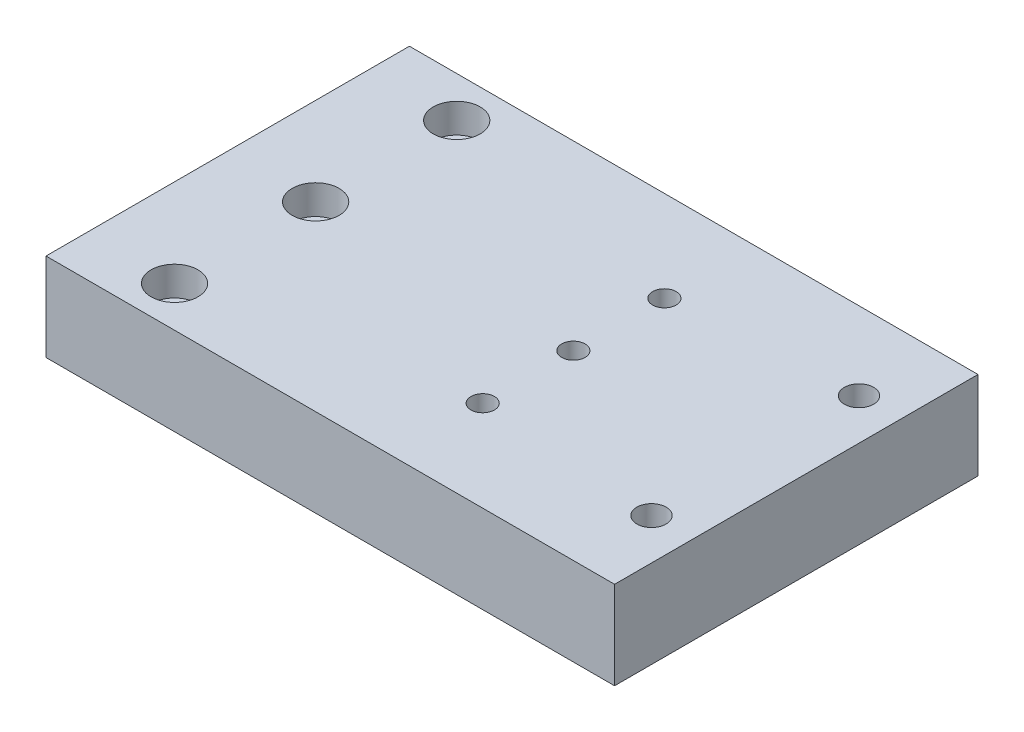
SolidWorks part; units mm, degrees
ref_plane "Plano frontal" through (0, 0, 0) normal (0, 0, 1) x (1, 0, 0)
ref_plane "Plano superior" through (0, 0, 0) normal (0, 1, 0) x (1, 0, 0)
ref_plane "Plano direito" through (0, 0, 0) normal (1, 0, 0) x (0, 0, -1)
sketch "Esboço1" plane through (0, 0, 0) normal (0, 1, 0) x (1, 0, 0)
  line L1 (0, 0) -> (67, 0)
  line L2 (0, 0) -> (0, -62)
  line L3 (0, -62) -> (67, -62)
  line L4 (67, 0) -> (67, -62)
  dimension "D1" = 67
  dimension "D2" = 62
extrude "Ressalto-extrusão1" add sketch "Esboço1" along normal blind 15
sketch "Esboço2" plane through (0, 15, 0) normal (0, 1, 0) x (1, 0, 0)
  line L7 (67, -62) -> (67, 0) construction
  line L8 (67, 0) -> (0, 0) construction
  line L10 (0, -62) -> (67, -62) construction
  circle A6 centre (60, -13.3) radius 2.5
  circle A7 centre (60, -48.7) radius 2.5
  circle A8 centre (29, -46.5) radius 2
  circle A9 centre (28.9706, -31) radius 2
  circle A10 centre (29, -15.5) radius 2
  dimension "D19" = 5
  dimension "D20" = 5
  dimension "D17" = 4
  dimension "D22" = 4
  dimension "D23" = 4
  dimension "D16" = 13.3
  dimension "13.3" = 13.3
  dimension "D18" = 7
  dimension "D21" = 7
extrude "Corte-extrusão1" cut sketch "Esboço2" against normal through all
sketch "Esboço3" plane through (0, 0, 0) normal (-1, 0, 0) x (0, 0, 1)
  line L1 (0, 0) -> (62, 0)
  line L2 (0, 0) -> (0, 15)
  line L3 (0, 15) -> (62, 15)
  line L4 (62, 0) -> (62, 15)
extrude "Ressalto-extrusão2" add sketch "Esboço3" along normal blind 30
sketch "Esboço4" plane through (0, 15, 0) normal (0, 1, 0) x (1, 0, 0)
  line L0 (67, 0) -> (-30, 0) construction
  line L2 (-30, -62) -> (67, -62) construction
  line L3 (-30, -62) -> (-30, 0) construction
  circle A0 centre (-15, -31) radius 2.5
  circle A1 centre (-15, -6.93) radius 2.5
  circle A2 centre (-15, -55.07) radius 2.5
  dimension "D3" = 5
  dimension "D4" = 5
  dimension "D5" = 5
  dimension "D1" = 6.93
  dimension "D2" = 6.93
  dimension "D6" = 15
  dimension "D7" = 15
  dimension "15" = 15
extrude "Corte-extrusão2" cut sketch "Esboço4" against normal through all
sketch "Esboço5" plane through (0, 15, 0) normal (0, 1, 0) x (1, 0, 0)
  circle A0 centre (-15, -6.93) radius 4
  circle A1 centre (-15, -31) radius 4
  circle A2 centre (-15, -55.07) radius 4
  dimension "D1" = 8
  dimension "D2" = 8
  dimension "D3" = 8
extrude "Corte-extrusão3" cut sketch "Esboço5" against normal blind 5
